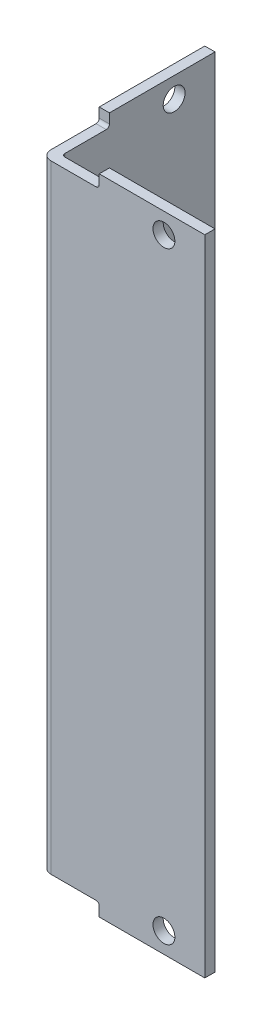
SolidWorks part; units mm, degrees
material "6061-T6 (SS)"
ref_plane "Front Plane" through (0, 0, 0) normal (0, 0, 1) x (1, 0, 0)
ref_plane "Top Plane" through (0, 0, 0) normal (0, 1, 0) x (1, 0, 0)
ref_plane "Right Plane" through (0, 0, 0) normal (1, 0, 0) x (0, 0, -1)
sketch "Sketch1" plane through (0, 0, 0) normal (0, 1, 0) x (1, 0, 0)
  line L1 (-12.7, -12.7) -> (12.7, -12.7)
  line L2 (-12.7, -12.7) -> (-12.7, 12.7)
  line L3 (-12.7, 12.7) -> (12.7, 12.7)
  line L4 (12.7, -12.7) -> (12.7, 12.7)
  line L5 (-12.7, -12.7) -> (12.7, 12.7) construction
  line L6 (-12.7, 12.7) -> (12.7, -12.7) construction
  point P0 (0, 0)
  dimension "D1" = 25.4
  dimension "D2" = 25.4
extrude "Boss-Extrude1" add sketch "Sketch1" along normal mid plane 113.5
sketch "Sketch2" plane through (0, 56.75, 0) normal (0, 1, 0) x (1, 0, 0)
  line L0 (-12.7, 12.7) -> (-12.7, -12.7) construction
  line L1 (12.7, 12.7) -> (-11.1125, 12.7)
  line L2 (12.7, 12.7) -> (12.7, -11.1125)
  line L3 (12.7, -11.1125) -> (-11.1125, -11.1125)
  line L4 (-11.1125, 12.7) -> (-11.1125, -11.1125)
  line L5 (-12.7, -12.7) -> (12.7, -12.7) construction
  dimension "D1" = 1.5875
  dimension "D2" = 1.5875
extrude "Cut-Extrude1" cut sketch "Sketch2" against normal through all
fillet "Fillet1" radius 0.508 1 edges at (-11.1125, 0, 11.1125)
hole_wizard "M3 Clearance Hole1" positions "Sketch3" profile "Sketch4" hole size "M3" standard "ANSI Metric" end condition through all
sketch "Sketch3" plane through (0, 0, 12.7) normal (0, 0, 1) x (1, 0, 0)
  line L1 (-12.7, 56.75) -> (12.7, 56.75) construction
  line L2 (12.7, 56.75) -> (12.7, -56.75) construction
  point P0 (6.35, 47.075)
  dimension "D1" = 6.35
  dimension "D2" = 9.675
sketch "Sketch4" plane through (6.35, 47.075, 12.7) normal (1, 0, 0) x (0, -1, 0)
  line L0 (0, 0) -> (0, 25.4)
  line L1 (0, 25.4) -> (1.7, 25.4)
  line L2 (1.7, 25.4) -> (1.7, 0)
  line L5 (1.7, 0) -> (0, 0)
  line L11 (0, -6.35) -> (0, 107.95) construction
  dimension "Thru Hole Dia." = 3.4
  dimension "Thru Hole Depth" = 25.4
hole_wizard "M3 Clearance Hole2" positions "Sketch5" profile "Sketch6" hole size "M3" standard "ANSI Metric" end condition through all
sketch "Sketch5" plane through (-12.7, 0, 0) normal (-1, 0, 0) x (0, 0, 1)
  line L1 (-12.7, 56.75) -> (12.7, 56.75) construction
  line L2 (-12.7, 56.75) -> (-12.7, -56.75) construction
  point P0 (-6.35, 47.075)
  dimension "D1" = 6.35
  dimension "D2" = 9.675
sketch "Sketch6" plane through (-12.7, 47.075, -6.35) normal (0, 1, 0) x (0, 0, 1)
  line L0 (0, 0) -> (0, 25.4)
  line L1 (0, 25.4) -> (1.7, 25.4)
  line L2 (1.7, 25.4) -> (1.7, 0)
  line L5 (1.7, 0) -> (0, 0)
  line L11 (0, -6.35) -> (0, 107.95) construction
  dimension "Thru Hole Dia." = 3.4
  dimension "Thru Hole Depth" = 25.4
hole_wizard "M3 Clearance Hole3" positions "Sketch7" profile "Sketch8" hole size "M3" standard "ANSI Metric" end condition through all
sketch "Sketch7" plane through (0, 0, 12.7) normal (0, 0, 1) x (1, 0, 0)
  line L2 (-12.7, -56.75) -> (12.7, -56.75) construction
  line L3 (12.7, 56.75) -> (12.7, -56.75) construction
  point P0 (6.35, -46.575)
  dimension "D1" = 6.35
  dimension "D2" = 10.175
sketch "Sketch8" plane through (6.35, -46.575, 12.7) normal (1, 0, 0) x (0, -1, 0)
  line L0 (0, 0) -> (0, 25.4)
  line L1 (0, 25.4) -> (1.7, 25.4)
  line L2 (1.7, 25.4) -> (1.7, 0)
  line L5 (1.7, 0) -> (0, 0)
  line L11 (0, -6.35) -> (0, 107.95) construction
  dimension "Thru Hole Dia." = 3.4
  dimension "Thru Hole Depth" = 25.4
hole_wizard "M3 Clearance Hole4" positions "Sketch9" profile "Sketch10" hole size "M3" standard "ANSI Metric" end condition through all
sketch "Sketch9" plane through (-12.7, 0, 0) normal (-1, 0, 0) x (0, 0, 1)
  line L1 (-12.7, -56.75) -> (12.7, -56.75) construction
  line L2 (-12.7, 56.75) -> (-12.7, -56.75) construction
  point P0 (-6.35, -46.575)
  dimension "D1" = 6.35
  dimension "D2" = 10.175
sketch "Sketch10" plane through (-12.7, -46.575, -6.35) normal (0, 1, 0) x (0, 0, 1)
  line L0 (0, 0) -> (0, 25.4)
  line L1 (0, 25.4) -> (1.7, 25.4)
  line L2 (1.7, 25.4) -> (1.7, 0)
  line L5 (1.7, 0) -> (0, 0)
  line L11 (0, -6.35) -> (0, 107.95) construction
  dimension "Thru Hole Dia." = 3.4
  dimension "Thru Hole Depth" = 25.4
fillet "Fillet2" radius 1.5 1 edges at (-12.7, 0, 12.7)
sketch "Sketch11" plane through (-12.7, 0, 0) normal (-1, 0, 0) x (0, 0, 1)
  line L0 (12.7, 56.75) -> (12.7, -56.75) construction
  line L1 (-12.7, 56.75) -> (4.2, 56.75)
  line L2 (-12.7, 56.75) -> (-12.7, 50.25)
  line L3 (-12.7, 50.25) -> (4.2, 50.25)
  line L4 (4.2, 56.75) -> (4.2, 50.25)
  line L6 (-12.7, -56.75) -> (4.2, -56.75)
  line L7 (-12.7, -56.75) -> (-12.7, -49.75)
  line L8 (-12.7, -49.75) -> (4.2, -49.75)
  line L9 (4.2, -56.75) -> (4.2, -49.75)
  dimension "D1" = 8.5
  dimension "D2" = 6.5
  dimension "D3" = 7
extrude "Cut-Extrude2" cut sketch "Sketch11" against normal up to next
sketch "Sketch12" plane through (0, 0, 12.7) normal (0, 0, 1) x (1, 0, 0)
  line L0 (-12.7, -56.75) -> (-12.7, 56.75) construction
  line L1 (12.7, 56.75) -> (-4.2, 56.75)
  line L2 (12.7, 56.75) -> (12.7, 50.25)
  line L3 (12.7, 50.25) -> (-4.2, 50.25)
  line L4 (-4.2, 56.75) -> (-4.2, 50.25)
  line L5 (12.7, -56.75) -> (-4.2, -56.75)
  line L6 (12.7, -56.75) -> (12.7, -49.75)
  line L7 (12.7, -49.75) -> (-4.2, -49.75)
  line L8 (-4.2, -56.75) -> (-4.2, -49.75)
  dimension "D1" = 8.5
  dimension "D2" = 7
  dimension "D3" = 8.5
  dimension "D4" = 6.5
extrude "Cut-Extrude3" cut sketch "Sketch12" against normal up to next
fillet "Fillet3" radius 3.81 4 edges at (-4.2, -49.75, 11.9062) (-11.9063, -49.75, 4.2) (-11.9063, 50.25, 4.2) (-4.2, 50.25, 11.9062)
sketch "Sketch13" plane through (-12.7, 0, 0) normal (-1, 0, 0) x (0, 0, 1)
  line L0 (4.2, -56.75) -> (4.2, 56.75) construction
  line L9 (2.7, -56.75) -> (2.7, 56.75) construction
  line L10 (-12.7, 50.25) -> (-12.7, -49.75) construction
  line L11 (2.7, -43.4) -> (-12.7, -43.4)
  line L12 (2.7, -43.4) -> (2.7, 43.9)
  line L13 (2.7, 43.9) -> (-12.7, 43.9)
  line L14 (-12.7, -43.4) -> (-12.7, 43.9)
  circle A2 centre (-6.35, 47.075) radius 1.7 construction
  circle A3 centre (-6.35, -46.575) radius 1.7 construction
  dimension "D2" = 3.175
  dimension "D3" = 3.175
  dimension "D1" = 1.5
extrude "Cut-Extrude4" cut sketch "Sketch13" against normal up to next
sketch "Sketch14" plane through (0, 0, 12.7) normal (0, 0, 1) x (1, 0, 0)
  line L0 (-4.2, 56.75) -> (-4.2, -56.75) construction
  line L1 (-2.7, 56.75) -> (-2.7, -56.75) construction
  line L2 (12.7, 50.25) -> (12.7, -49.75) construction
  line L3 (-2.7, -43.4) -> (12.7, -43.4)
  line L4 (-2.7, -43.4) -> (-2.7, 43.9)
  line L5 (-2.7, 43.9) -> (12.7, 43.9)
  line L6 (12.7, -43.4) -> (12.7, 43.9)
  circle A0 centre (6.35, 47.075) radius 1.7 construction
  circle A1 centre (6.35, -46.575) radius 1.7 construction
  dimension "D2" = 3.175
  dimension "D3" = 3.175
  dimension "D1" = 1.5
extrude "Cut-Extrude5" cut sketch "Sketch14" against normal up to next
chamfer "Chamfer2" distance 6.35 angle 45 4 edges at (-11.9063, 43.9, 2.7) (-2.7, 43.9, 11.9062) (-2.7, -43.4, 11.9062) (-11.9062, -43.4, 2.7)
fillet "Fillet5" radius 3.81 8 edges at (3.65, -43.4, 11.9062) (-2.7, -37.05, 11.9062) (-11.9063, -43.4, -3.65) (-11.9063, -37.05, 2.7) (-11.9063, 43.9, -3.65) (-11.9063, 37.55, 2.7) (-2.7, 37.55, 11.9062) (3.65, 43.9, 11.9062)
sketch "Sketch15" plane through (0, 56.75, 0) normal (0, 1, 0) x (1, 0, 0)
  line L0 (-11.2, -12.7) -> (-4.2, -12.7) construction
  line L1 (-12.7, -12.7) -> (-0.39, -12.7)
  line L2 (-12.7, -12.7) -> (-12.7, -0.39)
  line L3 (-12.7, -0.39) -> (-0.39, -0.39)
  line L4 (-0.39, -12.7) -> (-0.39, -0.39)
  line L5 (-12.7, -4.2) -> (-12.7, -11.2) construction
  line L6 (-0.39, -11.1125) -> (-0.39, -12.7) construction
extrude "Cut-Extrude6" cut sketch "Sketch15" against normal up to surface (6.5 mm away) up to face at (6.155, 50.25, 11.9062)
sketch "Sketch16" plane through (0, 50.25, 0) normal (0, 1, 0) x (1, 0, 0)
  line L0 (-11.2, -12.7) -> (12.7, -12.7) construction
  line L1 (-12.7, -12.7) -> (-5.7, -12.7)
  line L2 (-12.7, -12.7) -> (-12.7, -5.7)
  line L3 (-12.7, -5.7) -> (-5.7, -5.7)
  line L4 (-5.7, -12.7) -> (-5.7, -5.7)
  line L5 (-12.7, 12.7) -> (-12.7, -11.2) construction
  dimension "D1" = 7
  dimension "D2" = 7
sketch "Sketch17" plane through (0, -56.75, 0) normal (0, -1, 0) x (1, 0, 0)
  line L0 (-11.2, 12.7) -> (-4.2, 12.7) construction
  line L1 (-12.7, 12.7) -> (-0.39, 12.7)
  line L2 (-12.7, 12.7) -> (-12.7, 0.39)
  line L3 (-12.7, 0.39) -> (-0.39, 0.39)
  line L4 (-0.39, 12.7) -> (-0.39, 0.39)
  line L5 (-12.7, 4.2) -> (-12.7, 11.2) construction
  line L6 (-11.1125, 0.39) -> (-12.7, 0.39) construction
  line L7 (-0.39, 12.7) -> (-0.39, 11.1125) construction
extrude "Cut-Extrude8" cut sketch "Sketch17" against normal up to surface (7 mm away) up to face at (6.155, -49.75, 11.9062)
sketch "Sketch18" plane through (-12.7, 0, 0) normal (-1, 0, 0) x (0, 0, 1)
  line L0 (-12.7, -43.4) -> (-5.2282, -43.4) construction
  line L1 (5.7, -43.4) -> (11.2, -43.4)
  line L2 (5.7, -43.4) -> (5.7, -40.4)
  line L3 (5.7, -40.4) -> (11.2, -40.4)
  line L4 (11.2, -43.4) -> (11.2, -40.4)
  line L5 (12.7, 50.25) -> (12.7, -49.75) construction
  point P8 (8.45, -40.4)
  dimension "D1" = 5.5
  dimension "D2" = 3
  dimension "D3" = 4.25
sketch "Sketch19" plane through (0, -49.75, 0) normal (0, -1, 0) x (1, 0, 0)
  line L0 (12.7, 12.7) -> (-11.2, 12.7) construction
  line L1 (-12.7, 5.7) -> (-5.7, 5.7)
  line L2 (-12.7, 5.7) -> (-12.7, 12.7)
  line L3 (-12.7, 12.7) -> (-5.7, 12.7)
  line L4 (-5.7, 5.7) -> (-5.7, 12.7)
  line L5 (-12.7, 11.2) -> (-12.7, -12.7) construction
sketch "Sketch20" plane through (-12.7, 0, 0) normal (-1, 0, 0) x (0, 0, 1)
  line L0 (-12.7, 43.9) -> (-12.7, -43.4)
  line L14 (11.2, -49.75) -> (11.2, 50.25)
  line L15 (11.2, 50.25) -> (-12.7, 50.25)
  line L16 (-12.7, 50.25) -> (-12.7, 43.9)
  line L17 (-12.7, 43.9) -> (-5.2282, 43.9)
  line L18 (-2.5341, 42.7841) -> (1.5841, 38.6659)
  line L19 (2.7, 35.9718) -> (2.7, -35.4718)
  line L20 (1.5841, -38.1659) -> (-2.5341, -42.2841)
  line L21 (-5.2282, -43.4) -> (-12.7, -43.4)
  line L22 (-12.7, -43.4) -> (-12.7, -49.75)
  line L23 (-12.7, -49.75) -> (11.2, -49.75)
  line L27 (11.2, -49.75) -> (11.2, 50.25)
  line L28 (11.2, 50.25) -> (-12.7, 50.25)
  line L29 (-12.7, 50.25) -> (-12.7, 43.9)
  line L30 (-12.7, 43.9) -> (-5.2282, 43.9)
  line L31 (-2.5341, 42.7841) -> (1.5841, 38.6659)
  line L32 (2.7, 35.9718) -> (2.7, -35.4718)
  line L33 (1.5841, -38.1659) -> (-2.5341, -42.2841)
  line L34 (-5.2282, -43.4) -> (-12.7, -43.4)
  line L35 (-12.7, -43.4) -> (-12.7, -49.75)
  line L36 (-12.7, -49.75) -> (11.2, -49.75)
  arc A6 (-2.5341, 42.7841) -> (-5.2282, 43.9) centre (-5.2282, 40.09) ccw
  arc A7 (2.7, 35.9718) -> (1.5841, 38.6659) centre (-1.11, 35.9718) ccw
  arc A8 (1.5841, -38.1659) -> (2.7, -35.4718) centre (-1.11, -35.4718) ccw
  arc A9 (-5.2282, -43.4) -> (-2.5341, -42.2841) centre (-5.2282, -39.59) ccw
  arc A11 (-2.5341, 42.7841) -> (-5.2282, 43.9) centre (-5.2282, 40.09) ccw
  arc A12 (2.7, 35.9718) -> (1.5841, 38.6659) centre (-1.11, 35.9718) ccw
  arc A13 (1.5841, -38.1659) -> (2.7, -35.4718) centre (-1.11, -35.4718) ccw
  arc A14 (-5.2282, -43.4) -> (-2.5341, -42.2841) centre (-5.2282, -39.59) ccw
  line M26 (-12.7, 43.9) -> (-5.2282, 43.9)
  arc M27 (-5.2282, 43.9) -> (-2.5341, 42.7841) centre (-5.2282, 40.09) cw
  line M28 (-2.5341, 42.7841) -> (1.5841, 38.6659)
  arc M29 (1.5841, 38.6659) -> (2.7, 35.9718) centre (-1.11, 35.9718) cw
  line M30 (2.7, 35.9718) -> (2.7, -35.4718)
  arc M31 (2.7, -35.4718) -> (1.5841, -38.1659) centre (-1.11, -35.4718) cw
  line M32 (1.5841, -38.1659) -> (-2.5341, -42.2841)
  arc M33 (-2.5341, -42.2841) -> (-5.2282, -43.4) centre (-5.2282, -39.59) cw
  line M34 (-5.2282, -43.4) -> (-12.7, -43.4)
  dimension "D1" = 0
extrude "Boss-Extrude2" add sketch "Sketch20" against normal up to surface (1.5875 mm away) contours L0 M26 M34 M33 M32 M31 M30 M29 M28 M27 up to face at (-11.1125, -46.575, -4.65)
sketch "Sketch21" plane through (0, 0, 12.7) normal (0, 0, 1) x (1, 0, 0)
  line L0 (12.7, 43.9) -> (12.7, -43.4)
  line L14 (-11.2, 50.25) -> (-11.2, -49.75)
  line L15 (-11.2, -49.75) -> (12.7, -49.75)
  line L16 (12.7, -49.75) -> (12.7, -43.4)
  line L17 (12.7, -43.4) -> (5.2282, -43.4)
  line L18 (2.5341, -42.2841) -> (-1.5841, -38.1659)
  line L19 (-2.7, -35.4718) -> (-2.7, 35.9718)
  line L20 (-1.5841, 38.6659) -> (2.5341, 42.7841)
  line L21 (5.2282, 43.9) -> (12.7, 43.9)
  line L22 (12.7, 43.9) -> (12.7, 50.25)
  line L23 (12.7, 50.25) -> (-11.2, 50.25)
  line L27 (-11.2, 50.25) -> (-11.2, -49.75)
  line L28 (-11.2, -49.75) -> (12.7, -49.75)
  line L29 (12.7, -49.75) -> (12.7, -43.4)
  line L30 (12.7, -43.4) -> (5.2282, -43.4)
  line L31 (2.5341, -42.2841) -> (-1.5841, -38.1659)
  line L32 (-2.7, -35.4718) -> (-2.7, 35.9718)
  line L33 (-1.5841, 38.6659) -> (2.5341, 42.7841)
  line L34 (5.2282, 43.9) -> (12.7, 43.9)
  line L35 (12.7, 43.9) -> (12.7, 50.25)
  line L36 (12.7, 50.25) -> (-11.2, 50.25)
  arc A6 (2.5341, -42.2841) -> (5.2282, -43.4) centre (5.2282, -39.59) ccw
  arc A7 (-2.7, -35.4718) -> (-1.5841, -38.1659) centre (1.11, -35.4718) ccw
  arc A8 (-1.5841, 38.6659) -> (-2.7, 35.9718) centre (1.11, 35.9718) ccw
  arc A9 (5.2282, 43.9) -> (2.5341, 42.7841) centre (5.2282, 40.09) ccw
  arc A11 (2.5341, -42.2841) -> (5.2282, -43.4) centre (5.2282, -39.59) ccw
  arc A12 (-2.7, -35.4718) -> (-1.5841, -38.1659) centre (1.11, -35.4718) ccw
  arc A13 (-1.5841, 38.6659) -> (-2.7, 35.9718) centre (1.11, 35.9718) ccw
  arc A14 (5.2282, 43.9) -> (2.5341, 42.7841) centre (5.2282, 40.09) ccw
  line M24 (12.7, -43.4) -> (5.2282, -43.4)
  arc M25 (5.2282, -43.4) -> (2.5341, -42.2841) centre (5.2282, -39.59) cw
  line M26 (2.5341, -42.2841) -> (-1.5841, -38.1659)
  arc M27 (-1.5841, -38.1659) -> (-2.7, -35.4718) centre (1.11, -35.4718) cw
  line M28 (-2.7, -35.4718) -> (-2.7, 35.9718)
  arc M29 (-2.7, 35.9718) -> (-1.5841, 38.6659) centre (1.11, 35.9718) cw
  line M30 (-1.5841, 38.6659) -> (2.5341, 42.7841)
  arc M31 (2.5341, 42.7841) -> (5.2282, 43.9) centre (5.2282, 40.09) cw
  line M32 (5.2282, 43.9) -> (12.7, 43.9)
  dimension "D1" = 0
extrude "Boss-Extrude3" add sketch "Sketch21" against normal up to surface (1.5875 mm away) contours L0 M32 M31 M30 M29 M28 M27 M26 M25 M24 up to face at (8.05, -46.575, 11.1125)
sketch "Sketch23" plane through (-11.1125, 0, 0) normal (1, 0, 0) x (0, 0, -1)
  line L0 (-220.6296, -34.1208) -> (-227.7171, -34.1208)
  line L1 (-220.6296, -34.1208) -> (-220.6296, -41.1208)
  line L2 (-220.6296, -41.1208) -> (-227.7171, -41.1208)
  line L3 (-227.7171, -34.1208) -> (-227.7171, -41.1208)
  line L4 (-11.1125, -49.75) -> (-11.1125, 50.25) construction
  line L5 (-9.1125, 41.25) -> (-2.6125, 41.25)
  line L6 (-9.1125, 41.25) -> (-9.1125, 34.25)
  line L7 (-9.1125, 34.25) -> (-2.6125, 34.25)
  line L8 (-2.6125, 41.25) -> (-2.6125, 34.25)
  line L9 (-10.6045, 50.25) -> (12.7, 50.25) construction
  dimension "D1" = 8.5
  dimension "D2" = 2
  dimension "D3" = 9
  dimension "D4" = 16
extrude "Cut-Extrude12" cut sketch "Sketch23" against normal up to next contours L8 L7 L6 L5
fillet "Fillet9" radius 1.5875 4 edges at (-11.9063, 34.25, 2.6125) (-11.9063, 41.25, 2.6125) (-11.9062, 41.25, 9.1125) (-11.9062, 34.25, 9.1125)
ref_plane "Plane1" through (0, 0.25, 0) normal (0, 1, 0) x (1, 0, 0)
mirror "Mirror3" about plane through (0, 0.25, 0) normal (0, 1, 0) of "Fillet9", "Cut-Extrude12"
sketch "Sketch24" plane through (-12.7, 0, 0) normal (-1, 0, 0) x (0, 0, 1)
  line L0 (4.2, 34.25) -> (7.525, 34.25) construction
  line L1 (2.6125, 35.8375) -> (2.6125, 39.6625) construction
  line L2 (4.2, 41.25) -> (7.525, 41.25) construction
  line L3 (9.1125, 35.8375) -> (9.1125, 39.6625) construction
  line L4 (4.2, 34.25) -> (7.525, 34.25)
  line L5 (2.6125, 35.8375) -> (2.6125, 39.6625)
  line L6 (4.2, 41.25) -> (7.525, 41.25)
  line L7 (9.1125, 35.8375) -> (9.1125, 39.6625)
  arc A0 (2.6125, 35.8375) -> (4.2, 34.25) centre (4.2, 35.8375) ccw construction
  arc A1 (4.2, 41.25) -> (2.6125, 39.6625) centre (4.2, 39.6625) ccw construction
  arc A2 (9.1125, 39.6625) -> (7.525, 41.25) centre (7.525, 39.6625) ccw construction
  arc A3 (7.525, 34.25) -> (9.1125, 35.8375) centre (7.525, 35.8375) ccw construction
  arc A4 (2.6125, 35.8375) -> (4.2, 34.25) centre (4.2, 35.8375) ccw
  arc A5 (4.2, 41.25) -> (2.6125, 39.6625) centre (4.2, 39.6625) ccw
  arc A6 (9.1125, 39.6625) -> (7.525, 41.25) centre (7.525, 39.6625) ccw
  arc A7 (7.525, 34.25) -> (9.1125, 35.8375) centre (7.525, 35.8375) ccw
extrude "Boss-Extrude4" add sketch "Sketch24" against normal up to surface (1.5875 mm away) up to face at (-11.1125, -37.25, 5.8625)
sketch "Sketch25" plane through (0, -49.75, 0) normal (0, -1, 0) x (1, 0, 0)
  line L0 (12.7, 12.7) -> (-11.2, 12.7) construction
  line L1 (-12.7, 11.2) -> (-12.7, -12.7) construction
  line L2 (12.7, 12.7) -> (-11.2, 12.7) construction
  line L3 (-12.7, 11.2) -> (-12.7, -12.7) construction
  line L4 (-12.7, 5.7) -> (-12.7, 12.7) construction
  line L5 (-12.7, 12.7) -> (-3.7, 12.7)
  line L6 (-12.7, 12.7) -> (-12.7, 3.7)
  line L7 (-12.7, 3.7) -> (-3.7, 3.7)
  line L8 (-3.7, 12.7) -> (-3.7, 3.7)
  dimension "D1" = 9
  dimension "D2" = 9
extrude "Cut-Extrude13" cut sketch "Sketch25" against normal blind 2
fillet "Fillet10" radius 0.5 2 edges at (-11.9062, -47.75, 3.7) (-3.7, -47.75, 11.9062)
mirror "Mirror4" about plane through (0, 0.25, 0) normal (0, 1, 0) of "Cut-Extrude13", "Fillet10"
